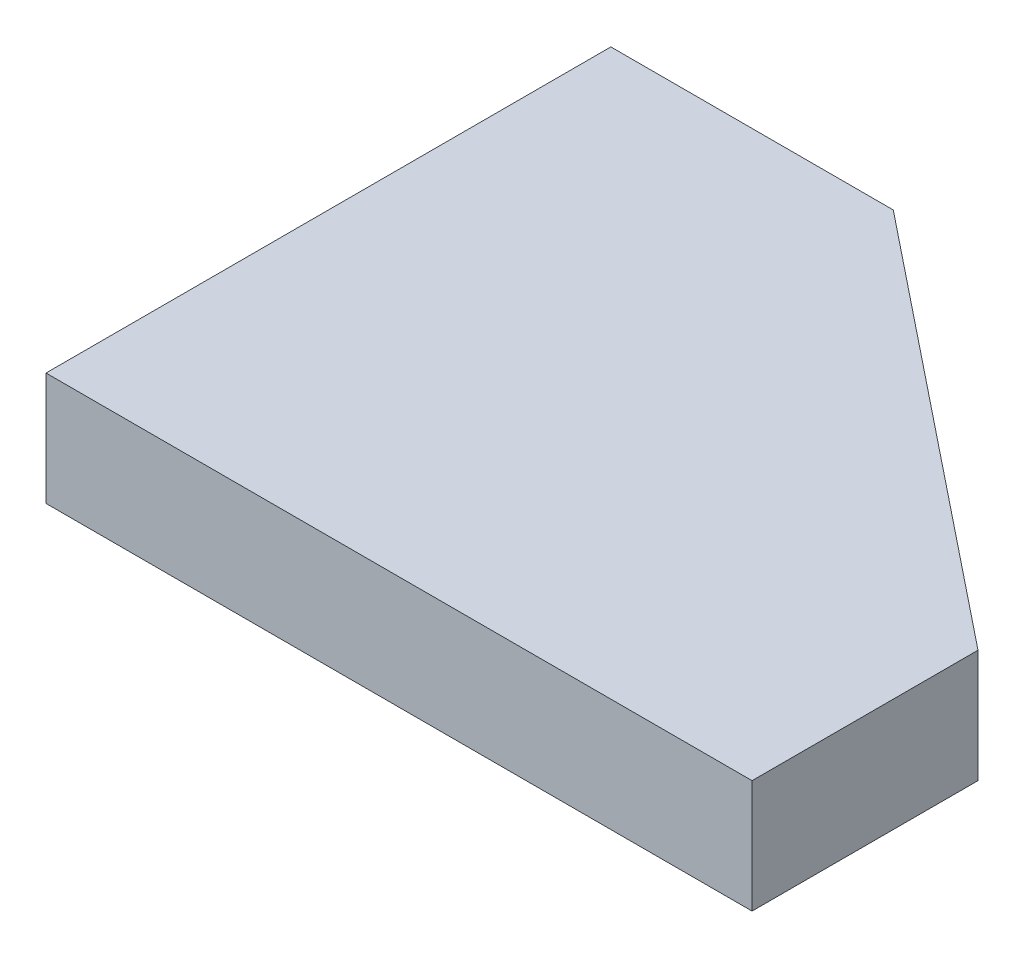
SolidWorks part; units mm, degrees
ref_plane "Спереди" through (0, 0, 0) normal (0, 0, 1) x (1, 0, 0)
ref_plane "Сверху" through (0, 0, 0) normal (0, 1, 0) x (1, 0, 0)
ref_plane "Справа" through (0, 0, 0) normal (1, 0, 0) x (0, 0, -1)
sketch "Эскиз1" plane through (0, 0, 0) normal (0, 1, 0) x (1, 0, 0)
  line L0 (0, 0) -> (0, 20)
  line L1 (0, 0) -> (25, 0)
  line L3 (25, 0) -> (25, 8)
  line L4 (25, 8) -> (10, 20)
  line L5 (10, 8) -> (10, 222) construction
  line L6 (10, 20) -> (0, 20)
extrude "Вытянуть1" add sketch "Эскиз1" along normal blind 4
